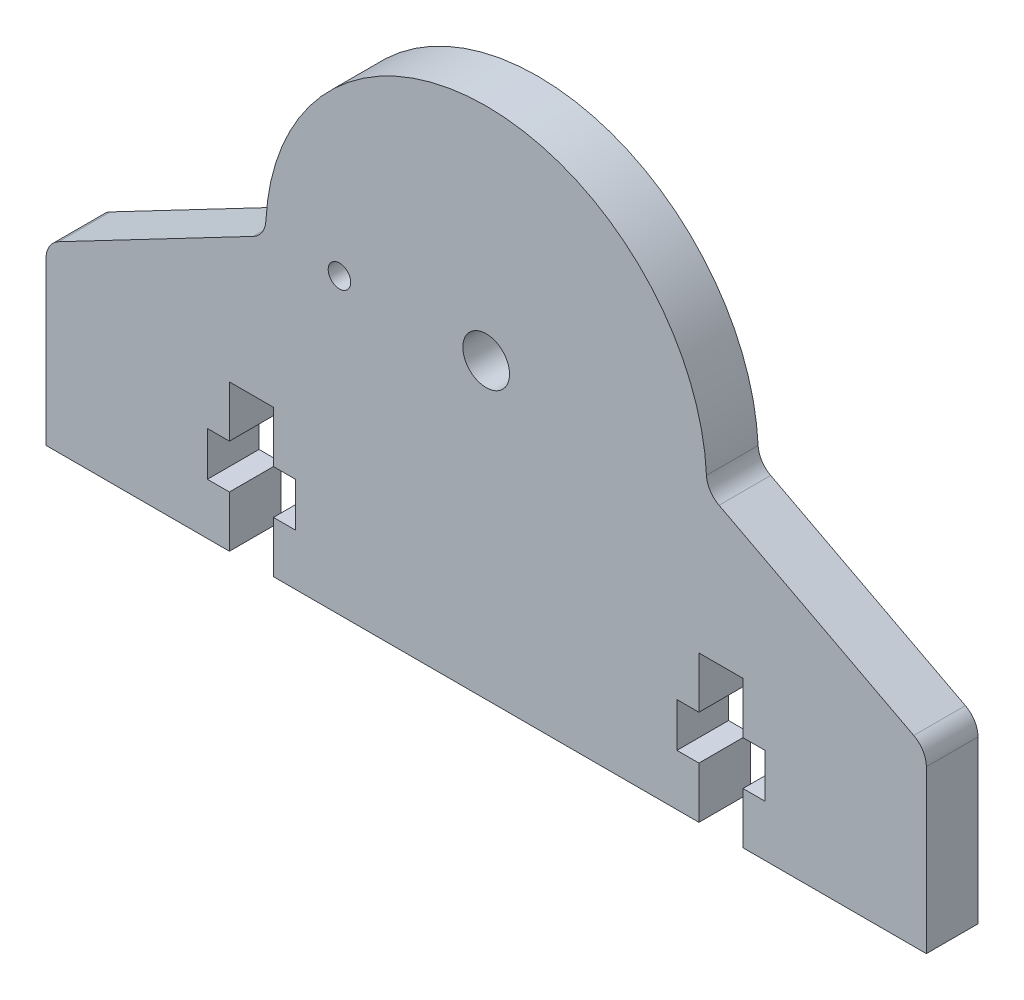
SolidWorks part; units mm, degrees
ref_plane "Front Plane" through (0, 0, 0) normal (0, 0, 1) x (1, 0, 0)
ref_plane "Top Plane" through (0, 0, 0) normal (0, 1, 0) x (1, 0, 0)
ref_plane "Right Plane" through (0, 0, 0) normal (1, 0, 0) x (0, 0, -1)
sketch "Sketch1" plane through (0, 0, 0) normal (0, 0, 1) x (1, 0, 0)
  line L0 (-23.8651, -0.254) -> (-47.625, -12.7)
  line L1 (-47.625, -12.7) -> (-47.625, -31.75)
  line L2 (-23.8651, 0) -> (-23.8651, -0.254)
  line L4 (23.8651, 0) -> (23.8651, -0.254)
  line L5 (-47.625, -31.75) -> (47.625, -31.75)
  line L6 (47.625, -31.75) -> (47.625, -12.7)
  line L7 (47.625, -12.7) -> (23.8651, -0.254)
  circle A0 centre (0, 0) radius 2.5273
  arc A1 (23.8651, 0) -> (-23.8651, 0) centre (0, 0) ccw
  circle A2 centre (0, 0) radius 23.8651 construction
  point P6 (0, 0)
  dimension "D1" = 47.7302
  dimension "D2" = 5.0546
  dimension "D3" = 95.25
  dimension "D4" = 19.05
  dimension "D5" = 0.254
  dimension "D6" = 31.75
extrude "Boss-Extrude1" add sketch "Sketch1" along normal mid plane 5.588
hole_wizard "#2 Clearance Hole1" positions "Sketch4" profile "Sketch3" hole size "#2" standard "ANSI Inch" end condition through all
sketch "Sketch4" plane through (0, 0, 2.794) normal (0, 0, 1) x (1, 0, 0)
  line L0 (-15.875, 0) -> (0, 0) construction
  point P0 (-15.875, 0)
  dimension "D1" = 15.875
sketch "Sketch3" plane through (-15.875, 0, 2.794) normal (1, 0, 0) x (0, -1, 0)
  line L0 (0, 0) -> (0, 5.588)
  line L1 (0, 5.588) -> (1.2192, 5.588)
  line L2 (1.2192, 5.588) -> (1.2192, 0)
  line L5 (1.2192, 0) -> (0, 0)
  line L11 (0, -6.35) -> (0, 107.95) construction
  dimension "Thru Hole Dia." = 2.4384
  dimension "Thru Hole Depth" = 5.588
fillet "Fillet1" radius 2.54 4 edges at (47.625, -12.7, 0) (23.8651, -0.254, 0) (-47.625, -12.7, 0) (-23.8651, -0.254, 0)
sketch "Sketch6" plane through (0, 0, 0) normal (0, 0, 1) x (1, 0, 0)
  line L0 (-47.625, -31.75) -> (47.625, -31.75) construction
  line L1 (0, 0) -> (0, -31.75) construction
  line L2 (-25.4, -31.75) -> (25.4, -31.75) construction
  line B0 (-27.7812, -31.75) -> (-27.7812, -26.1937)
  line B1 (-23.0187, -31.75) -> (-23.0187, -26.1937)
  line B2 (-27.7812, -15.875) -> (-23.0187, -15.875)
  line B3 (-27.7812, -31.75) -> (-23.0187, -31.75)
  line B4 (-30.1625, -26.1937) -> (-30.1625, -21.4313)
  line B5 (-30.1625, -26.1937) -> (-27.7812, -26.1937)
  line B6 (-20.6375, -26.1937) -> (-20.6375, -21.4313)
  line B7 (-30.1625, -21.4313) -> (-27.7812, -21.4313)
  line B8 (-23.0187, -26.1937) -> (-20.6375, -26.1937)
  line B9 (-23.0187, -21.4313) -> (-20.6375, -21.4313)
  line B10 (-27.7812, -21.4313) -> (-27.7812, -15.875)
  line B11 (-23.0187, -21.4313) -> (-23.0187, -15.875)
  line B12 (23.0188, -31.75) -> (23.0188, -26.1937)
  line B13 (27.7813, -31.75) -> (27.7813, -26.1937)
  line B14 (23.0188, -15.875) -> (27.7813, -15.875)
  line B15 (23.0188, -31.75) -> (27.7813, -31.75)
  line B16 (20.6375, -26.1937) -> (20.6375, -21.4313)
  line B17 (20.6375, -26.1937) -> (23.0188, -26.1937)
  line B18 (30.1625, -26.1937) -> (30.1625, -21.4313)
  line B19 (20.6375, -21.4313) -> (23.0188, -21.4313)
  line B20 (27.7813, -26.1937) -> (30.1625, -26.1937)
  line B21 (27.7813, -21.4313) -> (30.1625, -21.4313)
  line B22 (23.0188, -21.4313) -> (23.0188, -15.875)
  line B23 (27.7813, -21.4313) -> (27.7813, -15.875)
  dimension "D1" = 50.8
sketch_block_instance "Block2-1"
sketch_block "Block2" parameters "D1"=4.7625, "D2"=4.7625
sketch_block_instance "Block2-2"
extrude "Cut-Extrude2" cut sketch "Sketch6" against normal through all both and the other way through all
